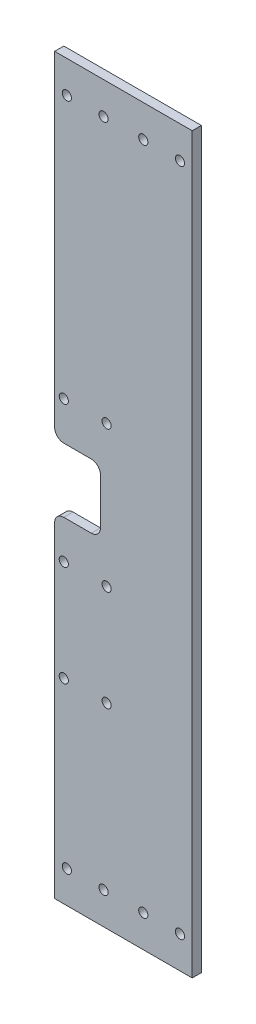
SolidWorks part; units mm, degrees
ref_plane "前视基准面" through (0, 0, 0) normal (0, 0, 1) x (1, 0, 0)
ref_plane "上视基准面" through (0, 0, 0) normal (0, 1, 0) x (1, 0, 0)
ref_plane "右视基准面" through (0, 0, 0) normal (1, 0, 0) x (0, 0, -1)
sketch "Model" plane through (0, 0, 0) normal (0, 0, 1) x (1, 0, 0)
  line L0 (2782.5103, 1858.2187) -> (2782.5103, 1843.2187)
  line L1 (2812.5103, 1970.7187) -> (2812.5103, 1730.7187)
  line L2 (2767.5103, 1970.7187) -> (2767.5103, 1864.2187)
  line L3 (2767.5103, 1837.2187) -> (2767.5103, 1730.7187)
  line L4 (2779.5103, 1861.2187) -> (2770.5103, 1861.2187)
  line L5 (2779.5103, 1840.2187) -> (2770.5103, 1840.2187)
  line L6 (2767.5103, 1730.7187) -> (2812.5103, 1730.7187)
  line L7 (2767.5103, 1970.7187) -> (2812.5103, 1970.7187)
  line L8 (2812.5103, 1744.7187) -> (2812.5103, 1730.7187)
  line L9 (2812.5103, 1730.7187) -> (2792.5103, 1730.7187)
  line L10 (2812.5103, 1732.2187) -> (2812.5103, 1737.2187)
  line L11 (2787.5103, 1730.7187) -> (2767.5103, 1730.7187)
  line L12 (2767.5103, 1730.7187) -> (2767.5103, 1744.7187)
  arc A0 (2779.5103, 1840.2187) -> (2782.5103, 1843.2187) centre (2779.5103, 1843.2187) ccw
  arc A1 (2782.5103, 1858.2187) -> (2779.5103, 1861.2187) centre (2779.5103, 1858.2187) ccw
  arc A2 (2770.5103, 1840.2187) -> (2767.5103, 1837.2187) centre (2770.5103, 1837.2187) ccw
  arc A3 (2767.5103, 1864.2187) -> (2770.5103, 1861.2187) centre (2770.5103, 1864.2187) ccw
  circle A4 centre (2808.5103, 1741.2187) radius 1.5
  circle A5 centre (2796.5103, 1741.2187) radius 1.5
  circle A6 centre (2783.5103, 1741.2187) radius 1.5
  circle A7 centre (2771.5103, 1741.2187) radius 1.5
  circle A8 centre (2808.5103, 1960.2187) radius 1.5
  circle A9 centre (2796.5103, 1960.2187) radius 1.5
  circle A10 centre (2783.5103, 1960.2187) radius 1.5
  circle A11 centre (2771.5103, 1960.2187) radius 1.5
  circle A12 centre (2784.5103, 1873.8187) radius 1.5
  circle A13 centre (2770.5103, 1873.8187) radius 1.5
  circle A14 centre (2770.5103, 1827.6187) radius 1.5
  circle A15 centre (2784.5103, 1827.6187) radius 1.5
extrude "凸台-拉伸1" add sketch "Model" along normal blind 3 contours L2 A3 L4 A1 L0 A0 L5 A2 L3 L6 L1 L8 L7 A15 A14 A13 A12 A11 A10 A9 A8 A7 A6 A5 A4
sketch "草图1" plane through (0, 0, 3) normal (0, 0, 1) x (1, 0, 0)
  line L0 (2767.5103, 1837.2187) -> (2767.5103, 1730.7187) construction
  circle A0 centre (2770.5103, 1794.6187) radius 1.5
  circle A1 centre (2784.5103, 1794.6187) radius 1.5
  circle A2 centre (2770.5103, 1827.6187) radius 1.5 construction
  dimension "D4" = 3
  dimension "D1" = 14
  dimension "D2" = 3
  dimension "D3" = 33
extrude "切除-拉伸1" cut sketch "草图1" against normal blind 10
